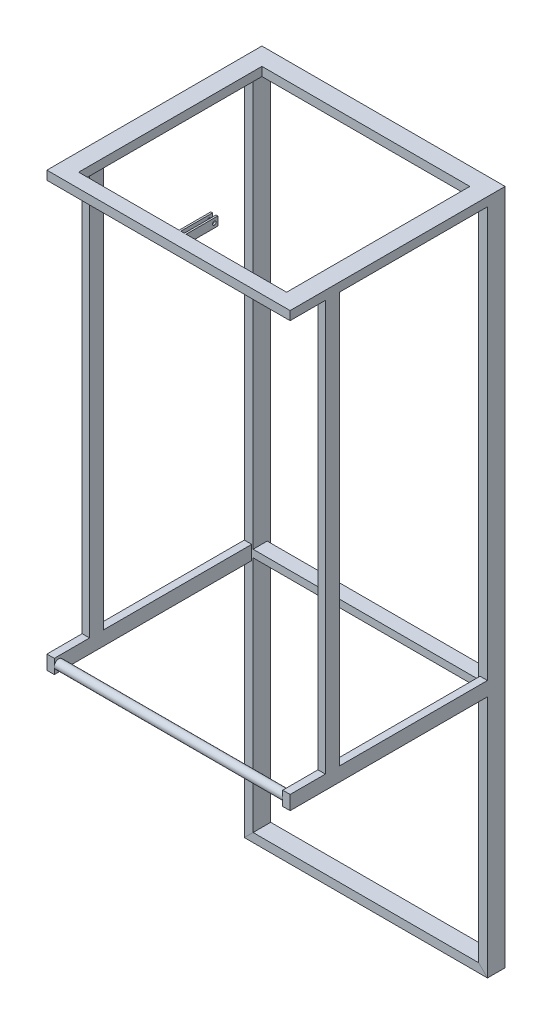
SolidWorks part; units mm, degrees
ref_plane "Front Plane" through (0, 0, 0) normal (0, 0, 1) x (1, 0, 0)
ref_plane "Top Plane" through (0, 0, 0) normal (0, 1, 0) x (1, 0, 0)
ref_plane "Right Plane" through (0, 0, 0) normal (1, 0, 0) x (0, 0, -1)
sketch "Sketch1" plane through (0, 0, 0) normal (0, 0, 1) x (1, 0, 0)
  line L0 (0, 1242.6978) -> (0, -1242.6978) construction
  line L1 (-345, -260) -> (345, -260)
  line L2 (-345, 960) -> (345, 960)
  line L3 (-345, 960) -> (-345, -960)
  line L4 (-345, -960) -> (345, -960)
  line L5 (345, 960) -> (345, -960)
  line L6 (-345, 960) -> (345, -960) construction
  line L7 (-345, -960) -> (345, 960) construction
  point P3 (0, 0)
  dimension "D1" = 1920
  dimension "D2" = 690
  dimension "D3" = 700
ref_plane "Plane2" through (-345, 960, 0) normal (1, 0, 0) x (0, 0, -1)
sketch "Sketch5" plane through (-345, 960, 0) normal (1, 0, 0) x (0, 0, -1)
  line L0 (0, 0) -> (0, -1920) construction
  line L1 (0, 0) -> (50, 0)
  line L2 (0, 0) -> (0, -25)
  line L3 (0, -25) -> (50, -25)
  line L4 (50, 0) -> (50, -25)
  dimension "D1" = 25
  dimension "D2" = 50
  dimension "D3" = 0
sweep "Sweep3" add profiles "Sketch5" path "Sketch1"
sketch "Sketch6" plane through (0, 0, 0) normal (0, 0, 1) x (1, 0, 0)
  line L0 (-345, -260) -> (345, -260)
  line L1 (-345, -960) -> (-345, 960) construction
  line L2 (345, 960) -> (345, -960) construction
  line L3 (345, -960) -> (-345, -960) construction
  dimension "D1" = 700
ref_plane "Plane3" through (345, -260, 0) normal (1, 0, 0) x (0, 0, -1)
sketch "Sketch7" plane through (345, -260, 0) normal (1, 0, 0) x (0, 0, -1)
  line L1 (0, 0) -> (40, 0)
  line L2 (0, 0) -> (0, 21)
  line L3 (0, 21) -> (40, 21)
  line L4 (40, 0) -> (40, 21)
  dimension "D1" = 21
  dimension "D2" = 40
sweep "Sweep4" add profiles "Sketch7" path "Sketch6"
sketch "Sketch9" plane through (0, 0, 0) normal (0, 0, 1) x (1, 0, 0)
  line L1 (345, -249) -> (-345, -249) construction
  line L2 (345, 960) -> (345, -960) construction
  line L3 (-345, -960) -> (-345, 960) construction
  line L4 (-320, -239) -> (320, -239) construction
  line L5 (324, -229) -> (345, -229)
  line L6 (324, -229) -> (324, -269)
  line L7 (324, -269) -> (345, -269)
  line L8 (345, -229) -> (345, -269)
  line L9 (324, -229) -> (345, -269) construction
  line L10 (324, -269) -> (345, -229) construction
  point P8 (334.5, -249)
  dimension "D1" = 10
  dimension "D2" = 21
  dimension "D3" = 40
extrude "Boss-Extrude2" add sketch "Sketch9" along normal blind 560 contours L5 L8 L7 L6
ref_plane "Plane5" through (0, 0, 0) normal (1, 0, 0) x (0, 0, -1)
mirror "Mirror1" about plane through (0, 0, 0) normal (1, 0, 0) of "Boss-Extrude2"
sketch "Sketch10" plane through (0, 0, 0) normal (0, 0, 1) x (1, 0, 0)
  line L0 (345, 960) -> (-345, 960) construction
  line L2 (345, 960) -> (295, 960)
  line L3 (345, 960) -> (345, 935)
  line L4 (345, 935) -> (295, 935)
  line L5 (295, 960) -> (295, 935)
  dimension "D1" = 25
  dimension "D2" = 50
extrude "Boss-Extrude3" add sketch "Sketch10" along normal blind 560
ref_plane "Plane7" through (0, 0, 0) normal (0, 0, -1) x (0, 1, 0)
mirror "Mirror3" about plane through (0, 0, 0) normal (1, 0, 0) of "Boss-Extrude3"
sketch "Sketch11" plane through (-295, 0, 0) normal (1, 0, 0) x (0, 0, -1)
  line L0 (-560, 935) -> (0, 935) construction
  line L1 (-560, 960) -> (-520, 960)
  line L2 (-560, 960) -> (-560, 935)
  line L3 (-560, 935) -> (-520, 935)
  line L4 (-520, 960) -> (-520, 935)
  dimension "D1" = 40
extrude "Boss-Extrude4" add sketch "Sketch11" along normal up to surface (590 mm away) up to face at (295, 947.5, 280)
ref_plane "Plane8" through (0, 350, 0) normal (0, 1, 0) x (1, 0, 0)
sketch "Sketch13" plane through (0, -229, 0) normal (0, 1, 0) x (1, 0, 0)
  line L0 (-345, -560) -> (-345, 0) construction
  line L1 (-345, -460) -> (-324, -460)
  line L2 (-345, -460) -> (-345, -420)
  line L3 (-345, -420) -> (-324, -420)
  line L4 (-324, -460) -> (-324, -420)
  line L5 (-324, -560) -> (-324, 0) construction
  line L6 (324, -560) -> (345, -560) construction
  dimension "D1" = 40
  dimension "D2" = 100
extrude "Boss-Extrude7" add sketch "Sketch13" along normal up to surface (1164 mm away) contours L1 L4 L3 L2
mirror "Mirror7" about plane through (0, 0, 0) normal (1, 0, 0) of "Boss-Extrude7"
sketch "Sketch19" plane through (-324, 0, 0) normal (1, 0, 0) x (0, 0, -1)
  line L0 (-560, -249) -> (-439.1694, -249) construction
  line L1 (-560, -229) -> (-560, -269) construction
  circle A0 centre (-547.5, -249) radius 12.5
  dimension "D1" = 25
extrude "Boss-Extrude11" add sketch "Sketch19" along normal up to next contours A0
sketch "Sketch20" plane through (0, 0, -50) normal (0, 0, -1) x (-1, 0, 0)
  line L1 (-332.5, -910) -> (-332.5, -985) construction
  line L2 (-360, -947.5) -> (-305, -947.5) construction
  line L3 (-345, -960) -> (-320, -935) construction
  line L4 (-332.5, -947.5) -> (-332.5, -937.3859) construction
  line L8 (-308, -985) -> (-357, -985)
  line L9 (-305, -982) -> (-305, -913)
  line L10 (-308, -910) -> (-357, -910)
  line L11 (-360, -982) -> (-360, -913)
  circle A0 centre (-315, -917) radius 3
  circle A1 centre (-350, -917) radius 3
  circle A2 centre (-350, -978) radius 3
  circle A3 centre (-315, -978) radius 3
  arc A4 (-305, -913) -> (-308, -910) centre (-308, -913) ccw
  arc A5 (-357, -910) -> (-360, -913) centre (-357, -913) ccw
  arc A6 (-357, -985) -> (-360, -982) centre (-357, -982) cw
  arc A7 (-308, -985) -> (-305, -982) centre (-308, -982) ccw
  point P6 (-332.5, -947.5)
  dimension "D3" = 6
  dimension "D7" = 3
  dimension "D1" = 55
  dimension "D2" = 75
  dimension "D4" = 10
  dimension "D5" = 7
  dimension "D6" = 10
extrude "Boss-Extrude12" [suppressed] add sketch "Sketch20" along normal blind 3
mirror "Mirror9" [suppressed] about plane through (0, 0, 0) normal (1, 0, 0)
ref_plane "Plane10" through (0, 0, 0) normal (0, -1, 0) x (-1, 0, 0)
mirror "Mirror10" [suppressed] about plane through (0, 0, 0) normal (0, -1, 0)
sketch "Sketch21" plane through (0, 0, 520) normal (0, 0, -1) x (-1, 0, 0)
  line L0 (0, 960) -> (0, 935) construction
  line L1 (-295, 960) -> (295, 960) construction
  line L2 (-295, 935) -> (295, 935) construction
  line L3 (-5, 935) -> (-10, 935)
  line L4 (5, 960) -> (10, 960)
  line L5 (5, 960) -> (5, 935)
  line L6 (5, 935) -> (10, 935)
  line L7 (10, 960) -> (10, 935)
  line L8 (-10, 960) -> (-10, 935)
  line L9 (-5, 960) -> (-10, 960)
  line L10 (-5, 960) -> (-5, 935)
  point P10 (0, 947.5)
  dimension "D1" = 10
  dimension "D2" = 5
extrude "Boss-Extrude13" add sketch "Sketch21" along normal blind 90
sketch "Sketch22" plane through (-10, 0, 0) normal (-1, 0, 0) x (0, 0, 1)
  line L0 (430, 947.5) -> (473.8294, 947.5) construction
  line L1 (430, 935) -> (430, 960) construction
  circle A0 centre (440, 947.5) radius 5
  dimension "D1" = 10
  dimension "D2" = 10
extrude "Cut-Extrude1" cut sketch "Sketch22" against normal blind 90
